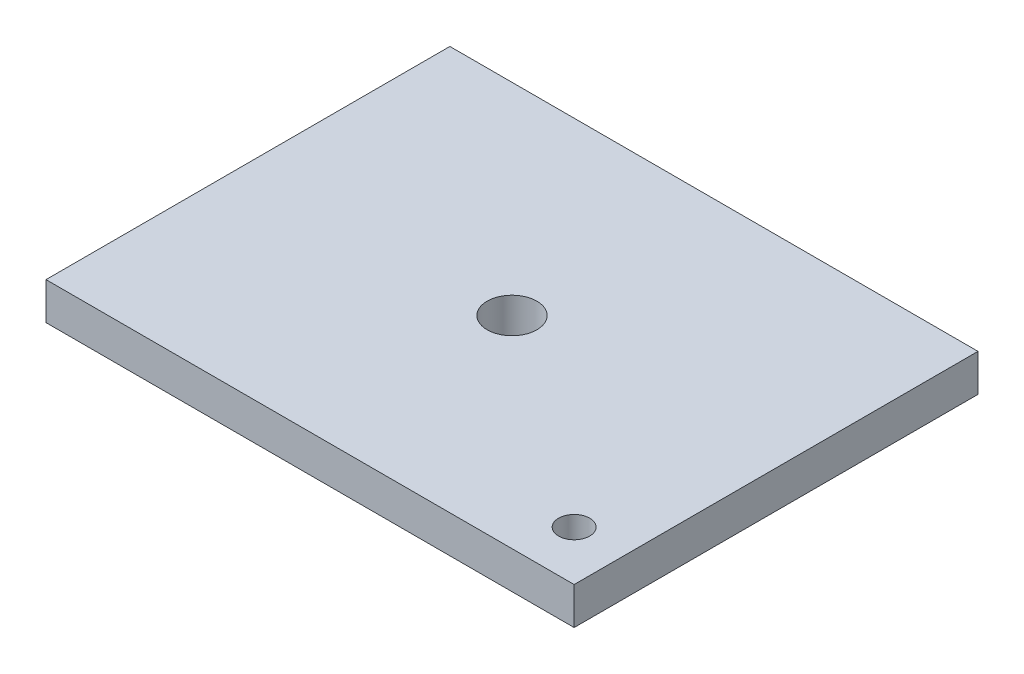
SolidWorks part; units mm, degrees
ref_plane "Спереди" through (0, 0, 0) normal (0, 0, 1) x (1, 0, 0)
ref_plane "Сверху" through (0, 0, 0) normal (0, 1, 0) x (1, 0, 0)
ref_plane "Справа" through (0, 0, 0) normal (1, 0, 0) x (0, 0, -1)
sketch "Эскиз1" plane through (0, 0, 0) normal (0, 1, 0) x (1, 0, 0)
  line L1 (0, 0) -> (85, 0)
  line L2 (0, 0) -> (0, -65)
  line L3 (0, -65) -> (85, -65)
  line L4 (85, 0) -> (85, -65)
  circle A0 centre (42.5, -32.5) radius 4
  dimension "D1" = 32.5
extrude "Вытянуть1" add sketch "Эскиз1" along normal blind 6
sketch "Эскиз2" plane through (0, 6, 0) normal (0, 1, 0) x (1, 0, 0)
  line L0 (85, -65) -> (85, 0) construction
  line L1 (0, -65) -> (85, -65) construction
  circle A0 centre (77, -57) radius 2.5
  dimension "D1" = 8
  dimension "D2" = 8
extrude "Вырез-Вытянуть1" cut sketch "Эскиз2" against normal through all
